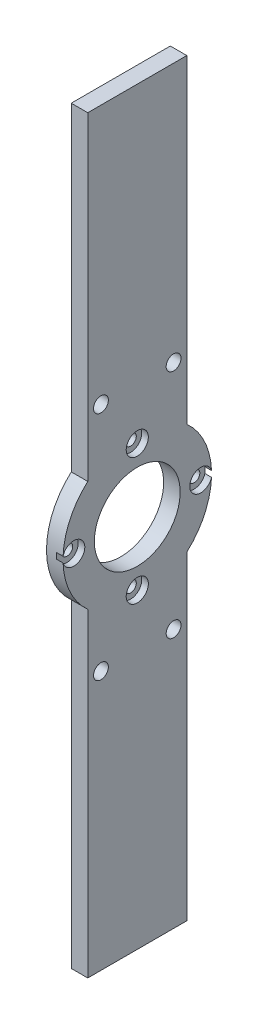
SolidWorks part; units mm, degrees
ref_plane "Спереди" through (0, 0, 0) normal (0, 0, 1) x (1, 0, 0)
ref_plane "Сверху" through (0, 0, 0) normal (0, 1, 0) x (1, 0, 0)
ref_plane "Справа" through (0, 0, 0) normal (1, 0, 0) x (0, 0, -1)
sketch "Эскиз1" plane through (0, 0, 0) normal (0, 1, 0) x (1, 0, 0)
  line L1 (0, 0) -> (5, 0)
  line L2 (0, 0) -> (0, -30)
  line L3 (0, -30) -> (5, -30)
  line L4 (5, 0) -> (5, -30)
  dimension "D1" = 5
  dimension "D2" = 30
extrude "Бобышка-Вытянуть1" add sketch "Эскиз1" along normal blind 227
sketch "Эскиз2" plane through (0, 0, 0) normal (-1, 0, 0) x (0, 0, 1)
  line L0 (30, 113.5) -> (0, 113.5) construction
  line L1 (30, 227) -> (30, 0) construction
  line L2 (0, 227) -> (0, 0) construction
  line L3 (15, 227) -> (15, 0) construction
  line L4 (0, 227) -> (30, 227) construction
  line L5 (0, 0) -> (30, 0) construction
  circle A0 centre (15, 113.5) radius 22.5
  dimension "D1" = 45
extrude "Бобышка-Вытянуть2" add sketch "Эскиз2" against normal up to surface (5 mm away) up to face at (5, 113.5, 15)
sketch "Эскиз3" plane through (0, 0, 0) normal (-1, 0, 0) x (0, 0, 1)
  circle A0 centre (15, 113.5) radius 13
  dimension "D1" = 26
extrude "Вырез-Вытянуть1" cut sketch "Эскиз3" against normal through all
sketch "Эскиз4" plane through (5, 0, 0) normal (-1, 0, 0) x (0, 0, 1)
  line L0 (15, 136) -> (15, 91) construction
  line L1 (15, 227) -> (15, 0) construction
  line L2 (37.5, 113.5) -> (-7.5, 113.5) construction
  circle A0 centre (15, 113.5) radius 19.25 construction
  circle A1 centre (15, 113.5) radius 22.5 construction
  dimension "D1" = 38.5
hole_wizard "Цековка для  винта с полукруглой головкой M31" positions "Эскиз6" profile "Эскиз5" counterbore size "M3" standard "Ansi Metric" end condition through all
sketch "Эскиз6" plane through (5, -25.0247, 7.2629) normal (-1, 0, 0) x (0, 0, 1)
  line L0 (7.7371, 161.0247) -> (7.7371, 116.0247) construction
  line L1 (30.2371, 138.5247) -> (-14.7629, 138.5247) construction
  circle A0 centre (7.7371, 138.5247) radius 19.25 construction
  point P0 (7.7371, 157.7747)
  point P6 (-11.5129, 138.5247)
  point P10 (7.7371, 119.2747)
  point P12 (26.9871, 138.5247)
sketch "Эскиз5" plane through (5, 132.75, 15) normal (0, 1, 0) x (0, 0, -1)
  line L0 (0, 0) -> (0, 5)
  line L1 (0, 5) -> (1.7, 5)
  line L3 (1.7, 5) -> (1.7, 2)
  line L4 (1.7, 2) -> (3.35, 2)
  line L5 (3.35, 2) -> (3.35, 0)
  line L7 (3.35, 0) -> (0, 0)
  line L11 (0, -6.35) -> (0, 107.95) construction
  dimension "Диаметр сквозного отверстия" = 3.4
  dimension "Глубина сквозного отверстия" = 5
  dimension "Диаметр цековки" = 6.7
  dimension "Глубина цековки" = 2
sketch "Эскиз8" plane through (5, 0, 0) normal (1, 0, 0) x (0, 0, -1)
  line L0 (-15, 227) -> (-15, 0) construction
  line L1 (-30, 227) -> (0, 227) construction
  line L2 (-30, 0) -> (0, 0) construction
  line L3 (19.447, 113.5) -> (-49.447, 113.5) construction
  line L4 (0, 227) -> (0, 130.2705) construction
  line L5 (-26, 148.5) -> (-4, 148.5) construction
  line L6 (-26, 148.5) -> (-26, 78.5) construction
  line L7 (-26, 78.5) -> (-4, 78.5) construction
  line L8 (-4, 148.5) -> (-4, 78.5) construction
  line L9 (-26, 148.5) -> (-4, 78.5) construction
  line L10 (-26, 78.5) -> (-4, 148.5) construction
  point P8 (-15, 113.5)
  point P9 (-15, 113.5)
  dimension "D1" = 4
  dimension "D2" = 70
hole_wizard "Отверстие с зазором M41" positions "Эскиз10" profile "Эскиз9" hole size "M4" standard "Ansi Metric" end condition through all
sketch "Эскиз10" plane through (5, 0, 0) normal (1, 0, 0) x (0, 0, -1)
  point P0 (-26, 148.5)
  point P3 (-4, 148.5)
  point P6 (-4, 78.5)
  point P9 (-26, 78.5)
sketch "Эскиз9" plane through (5, 148.5, 26) normal (0, 1, 0) x (0, 0, -1)
  line L0 (0, 0) -> (0, 5)
  line L1 (0, 5) -> (2.25, 5)
  line L2 (2.25, 5) -> (2.25, 0)
  line L5 (2.25, 0) -> (0, 0)
  line L11 (0, -6.35) -> (0, 107.95) construction
  dimension "Диаметр сквозного отверстия" = 4.5
  dimension "Глубина сквозного отверстия" = 5
